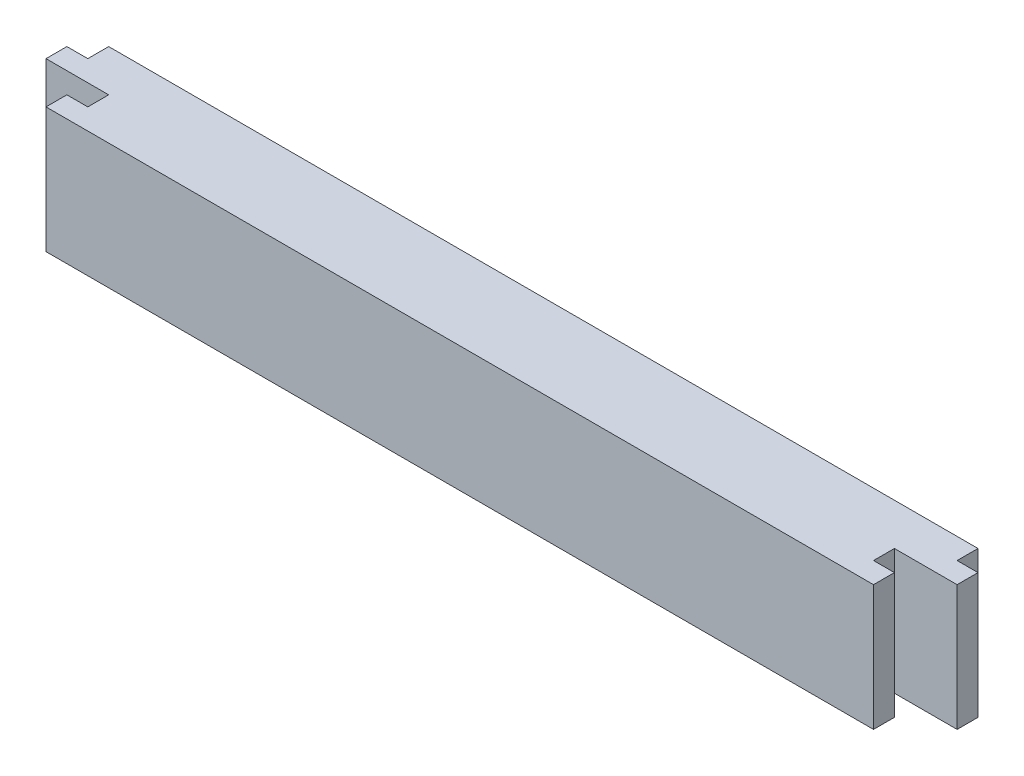
SolidWorks part; units mm, degrees
ref_plane "Alzado" through (0, 0, 0) normal (0, 0, 1) x (1, 0, 0)
ref_plane "Planta" through (0, 0, 0) normal (0, 1, 0) x (1, 0, 0)
ref_plane "Vista lateral" through (0, 0, 0) normal (1, 0, 0) x (0, 0, -1)
sketch "Tapa-Caja-Placas-Croquis" plane through (0, 0, 0) normal (0, 1, 0) x (1, 0, 0)
  line L0 (-55, 0) -> (55, 0) construction
  line L1 (-26, -1.25) -> (-23.5, -1.25)
  line L2 (-26, 0) -> (-26, 1.25)
  line L3 (-26, 1.25) -> (26, 1.25)
  line L4 (26, 0) -> (26, 1.25)
  line L5 (-26, -1.25) -> (26, 1.25) construction
  line L6 (-26, 1.25) -> (26, -1.25) construction
  line L7 (-26, -1.25) -> (-27.25, -1.25)
  line L9 (-26, 0) -> (-27.25, 0)
  line L10 (-27.25, -1.25) -> (-27.25, 0)
  line L11 (0, 0) -> (0, -2.5) construction
  line L12 (26, -1.25) -> (27.25, -1.25)
  line L14 (26, 0) -> (27.25, 0)
  line L15 (27.25, -1.25) -> (27.25, 0)
  line L16 (0, -55) -> (0, 55) construction
  line L17 (23.5, -1.25) -> (26, -1.25)
  line L18 (-23.5, -3.75) -> (23.5, -3.75)
  line L19 (-23.5, -2.5) -> (-23.5, -1.25)
  line L21 (23.5, -2.5) -> (23.5, -1.25)
  line L22 (-23.5, -3.75) -> (23.5, -1.25) construction
  line L23 (-23.5, -1.25) -> (23.5, -3.75) construction
  line L24 (23.5, -3.75) -> (24.75, -3.75)
  line L26 (23.5, -2.5) -> (24.75, -2.5)
  line L27 (24.75, -3.75) -> (24.75, -2.5)
  line L28 (-23.5, -3.75) -> (-24.75, -3.75)
  line L30 (-23.5, -2.5) -> (-24.75, -2.5)
  line L31 (-24.75, -3.75) -> (-24.75, -2.5)
  point P0 (0, 0)
  dimension "D1" = 52
  dimension "D2" = 2.5
  dimension "D3" = 1.25
  dimension "D4" = 1.25
  dimension "D5" = 2.5
  dimension "D6" = 47
  dimension "D7" = 1.25
  dimension "D8" = 1.25
extrude "Tapa-Caja-Placas-Saliente" add sketch "Tapa-Caja-Placas-Croquis" along normal blind 7.5
